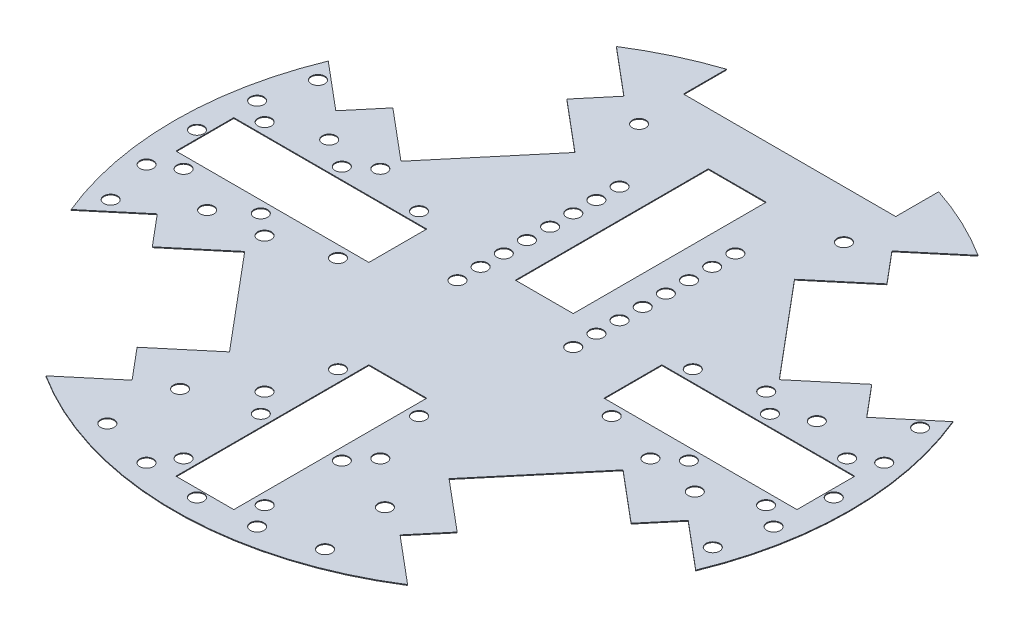
SolidWorks part; units mm, degrees
ref_plane "Front Plane" through (0, 0, 0) normal (0, 0, 1) x (1, 0, 0)
ref_plane "Top Plane" through (0, 0, 0) normal (0, 1, 0) x (1, 0, 0)
ref_plane "Right Plane" through (0, 0, 0) normal (1, 0, 0) x (0, 0, -1)
sketch "Sketch2" plane through (0, 0, 0) normal (0, 1, 0) x (1, 0, 0)
  line L12 (0, 0) -> (87.5, 0) construction
  line L13 (87.5, 0) -> (-87.5, 0) construction
  circle A0 centre (0, 0) radius 87.5
  dimension "D1" = 175
extrude "Boss-Extrude1" add sketch "Sketch2" along normal blind 0.2
ref_plane "Plane1" through (0, 10, 0) normal (0, 1, 0) x (1, 0, 0)
sketch "Sketch4" plane through (0, 10, 0) normal (0, 1, 0) x (1, 0, 0)
  line L0 (0, 0) -> (0, 87.5) construction
  line L1 (-27.5, 87.5) -> (27.5, 87.5) construction
  line L6 (-27.5, 103.07) -> (27.5, 103.07)
  line L7 (-27.5, 103.07) -> (-27.5, 71.93)
  line L8 (-27.5, 71.93) -> (27.5, 71.93)
  line L9 (27.5, 103.07) -> (27.5, 71.93)
  circle A0 centre (0, 0) radius 87.5 construction
  point P12 (0, 87.5)
  dimension "D1" = 55
  dimension "D2" = 15.57
extrude "Cut-Extrude1" cut sketch "Sketch4" against normal blind 173.2 contours L6 L9 L8 L7
sketch "Sketch5" plane through (0, 0.2, 0) normal (0, 1, 0) x (1, 0, 0)
  line L1 (-46.8471, 73.9027) -> (-34.7183, 63.7254)
  line L2 (-80.9148, 33.3023) -> (-68.7861, 23.1251)
  line L3 (-34.7183, 63.7254) -> (-41.4676, 55.6819)
  line L5 (-41.4676, 55.6819) -> (-28.4448, 44.7546)
  line L6 (-62.0368, 31.1685) -> (-49.014, 20.2411)
  line L7 (-28.4448, 44.7546) -> (-49.014, 20.2411)
  line L8 (0, 0) -> (-87.5, 0) construction
  line L9 (-62.0368, 31.1685) -> (-41.4676, 55.6819) construction
  line L10 (-38.7294, 32.4978) -> (0, 0) construction
  line L12 (-80.9148, 33.3023) -> (-94.8316, 44.9798)
  line L13 (-46.8471, 73.9027) -> (-60.7638, 85.5802)
  line L14 (-94.8316, 44.9798) -> (-60.7638, 85.5802)
  line L15 (-62.0368, 31.1685) -> (-68.7861, 23.1251)
  line L16 (-26.5383, 59.4724) -> (-63.1772, 15.8079) construction
  line L17 (-44.8578, 37.6401) -> (-38.7294, 32.4978) construction
  line L18 (-26.5383, 59.4724) -> (-26.5383, 61.2224) construction
  line L19 (-63.1772, 15.8079) -> (-63.1772, 17.5579) construction
  arc A0 (-27.5, 83.0662) -> (27.5, 83.0662) centre (0, 0) ccw construction
  circle A1 centre (-26.5383, 59.4724) radius 1.75
  circle A2 centre (-63.1772, 15.8079) radius 1.75
  dimension "D2" = 53
  dimension "D3" = 32
  dimension "D4" = 17
  dimension "D5" = 40
  dimension "D6" = 8
  dimension "D7" = 57
  dimension "D8" = 1.75
  dimension "D9" = 1.75
  dimension "D10" = 12.5
  dimension "D11" = 50.5577
  dimension "D12" = 18.167
extrude "Cut-Extrude3" cut sketch "Sketch5" against normal blind 183.2
mirror "Mirror2" about plane through (0, 0, 0) normal (0, 0, 1) of "Cut-Extrude3" second plane through (0, 0, 0) second plane normal (1, 0, 0)
ref_plane "Plane2" through (0, 10, 0) normal (0, 1, 0) x (1, 0, 0)
sketch "Sketch9" plane through (0, 10, 0) normal (0, 1, 0) x (1, 0, 0)
  line L0 (0, 0.875) -> (0, 58.375) construction
  line L1 (0, 8.375) -> (0, 0.875) construction
  line L2 (-7.5, 58.375) -> (7.5, 58.375)
  line L3 (-7.5, 58.375) -> (-7.5, 8.375)
  line L4 (-7.5, 8.375) -> (7.5, 8.375)
  line L5 (7.5, 58.375) -> (7.5, 8.375)
  line L6 (15, 0.875) -> (-15, 0.875) construction
  line L7 (-15, 0.875) -> (-15, 2.625) construction
  line L8 (-15, 0.875) -> (-15, 6.875) construction
  line L9 (15, 0.875) -> (15, 6.875) construction
  line L10 (0, 0.875) -> (-30.4635, 0.875) construction
  line L11 (-80.4635, -6.625) -> (-30.4635, -6.625)
  line L12 (-80.4635, -6.625) -> (-80.4635, 8.375)
  line L13 (-80.4635, 8.375) -> (-30.4635, 8.375)
  line L14 (-30.4635, -6.625) -> (-30.4635, 8.375)
  line L15 (-35.4635, 11.375) -> (-35.4635, -9.625) construction
  line L16 (-35.4635, 0.875) -> (-30.4635, 0.875) construction
  line L17 (-50, 15.875) -> (-50, -14.125) construction
  line L18 (-50, 0.875) -> (0, 0.875) construction
  line L19 (-78.0053, -25.9844) -> (0, 0.875) construction
  line L20 (0, 0.875) -> (-82.5, 0.875) construction
  line L21 (-81.2466, 15.201) -> (0, 0.875) construction
  line L22 (0, 0.875) -> (-81.2466, -13.451) construction
  line L23 (0, 0.875) -> (-78.0053, 27.7344) construction
  line L24 (7.5, -79.5885) -> (-7.5, -79.5885)
  line L25 (7.5, -79.5885) -> (7.5, -29.5885)
  line L26 (7.5, -29.5885) -> (-7.5, -29.5885)
  line L27 (-7.5, -79.5885) -> (-7.5, -29.5885)
  line L28 (80.4635, 8.375) -> (80.4635, -6.625)
  line L29 (80.4635, 8.375) -> (30.4635, 8.375)
  line L30 (30.4635, 8.375) -> (30.4635, -6.625)
  line L31 (80.4635, -6.625) -> (30.4635, -6.625)
  line L32 (0, 0.875) -> (78.0053, -25.9844) construction
  line L33 (78.0053, -25.9844) -> (0, 0.875) construction
  line L34 (0, 0.875) -> (81.2466, -13.451) construction
  line L35 (0, 0.875) -> (78.0053, 27.7344) construction
  line L36 (78.0053, 27.7344) -> (0, 0.875) construction
  line L37 (0, 0.875) -> (81.2466, 15.201) construction
  line L38 (0, 0.875) -> (82.5, 0.875) construction
  circle A0 centre (-15, 0.875) radius 1.75
  circle A1 centre (15, 0.875) radius 1.75
  circle A2 centre (15, 6.875) radius 1.75
  circle A3 centre (-15, 6.875) radius 1.75
  circle A4 centre (-15, 12.875) radius 1.75
  circle A5 centre (15, 12.875) radius 1.75
  circle A6 centre (-15, 18.875) radius 1.75
  circle A7 centre (15, 18.875) radius 1.75
  circle A8 centre (-15, 24.875) radius 1.75
  circle A9 centre (15, 24.875) radius 1.75
  circle A10 centre (-15, 30.875) radius 1.75
  circle A11 centre (15, 30.875) radius 1.75
  circle A12 centre (-15, 36.875) radius 1.75
  circle A13 centre (15, 36.875) radius 1.75
  circle A14 centre (-15, 42.875) radius 1.75
  circle A15 centre (15, 42.875) radius 1.75
  circle A16 centre (-35.4635, 11.375) radius 1.75
  circle A17 centre (-35.4635, -9.625) radius 1.75
  circle A18 centre (-55.4635, -9.625) radius 1.75
  circle A19 centre (-55.4635, 11.375) radius 1.75
  circle A20 centre (-75.4635, -9.625) radius 1.75
  circle A21 centre (-75.4635, 11.375) radius 1.75
  circle A22 centre (-50, -14.125) radius 1.75
  circle A23 centre (-50, 15.875) radius 1.75
  circle A24 centre (0, 0.875) radius 82.5 construction
  circle A25 centre (-82.5, 0.875) radius 1.75
  circle A26 centre (-78.0053, -25.9844) radius 1.75
  circle A27 centre (-81.2466, -13.451) radius 1.75
  circle A28 centre (-81.2466, 15.201) radius 1.75
  circle A29 centre (-78.0053, 27.7344) radius 1.75
  circle A30 centre (28.2167, -76.6496) radius 1.75
  circle A31 centre (14.326, -80.3716) radius 1.75
  circle A32 centre (10.5, -74.5885) radius 1.75
  circle A33 centre (10.5, -54.5885) radius 1.75
  circle A34 centre (15, -49.125) radius 1.75
  circle A35 centre (10.5, -34.5885) radius 1.75
  circle A36 centre (0, -81.625) radius 1.75
  circle A37 centre (-14.326, -80.3716) radius 1.75
  circle A38 centre (-28.2167, -76.6496) radius 1.75
  circle A39 centre (-10.5, -74.5885) radius 1.75
  circle A40 centre (-10.5, -54.5885) radius 1.75
  circle A41 centre (-15, -49.125) radius 1.75
  circle A42 centre (-10.5, -34.5885) radius 1.75
  circle A43 centre (78.0053, 27.7344) radius 1.75
  circle A44 centre (81.2466, 15.201) radius 1.75
  circle A45 centre (75.4635, 11.375) radius 1.75
  circle A46 centre (55.4635, 11.375) radius 1.75
  circle A47 centre (50, 15.875) radius 1.75
  circle A48 centre (35.4635, 11.375) radius 1.75
  circle A49 centre (82.5, 0.875) radius 1.75
  circle A50 centre (81.2466, -13.451) radius 1.75
  circle A51 centre (78.0053, -25.9844) radius 1.75
  circle A52 centre (75.4635, -9.625) radius 1.75
  circle A53 centre (55.4635, -9.625) radius 1.75
  circle A54 centre (50, -14.125) radius 1.75
  circle A55 centre (35.4635, -9.625) radius 1.75
  point P7 (0, 58.375)
  point P10 (0, 0.875)
  point P77 (0, 0.875)
  point P138 (0, 0.875)
  dimension "D26" = 2.0365
  dimension "D1" = 50
  dimension "D2" = 7.5
  dimension "D3" = 30
  dimension "D4" = 1.75
  dimension "D5" = 1.75
  dimension "D6" = 6
  dimension "D7" = 6
  dimension "D8" = 1.75
  dimension "D9" = 1.75
  dimension "D10" = 15
  dimension "D11" = 50
  dimension "D12" = 15
  dimension "D13" = 5
  dimension "D14" = 21
  dimension "D15" = 30
  dimension "D16" = 50
  dimension "D17" = 82.5
  dimension "D18" = 9
  dimension "D19" = 10
  dimension "D20" = 9
  dimension "D21" = 10
  dimension "D22" = 9
  dimension "D23" = 10
  dimension "D24" = 10
  dimension "D25" = 9
extrude "Cut-Extrude4" cut sketch "Sketch9" against normal blind 55 and the other way blind 39
sketch "Sketch10" plane through (0, 0.2, 0) normal (0, 1, 0) x (1, 0, 0)
  line L0 (-27.5, 83.0662) -> (27.5, 83.0662) construction
sketch "Sketch11" plane through (0, 0.2, 0) normal (0, 1, 0) x (1, 0, 0)
  line L0 (-27.5, 83.0662) -> (27.5, 83.0662) construction
  arc A0 (46.8471, 73.9027) -> (27.5, 83.0662) centre (0, 0) ccw construction
